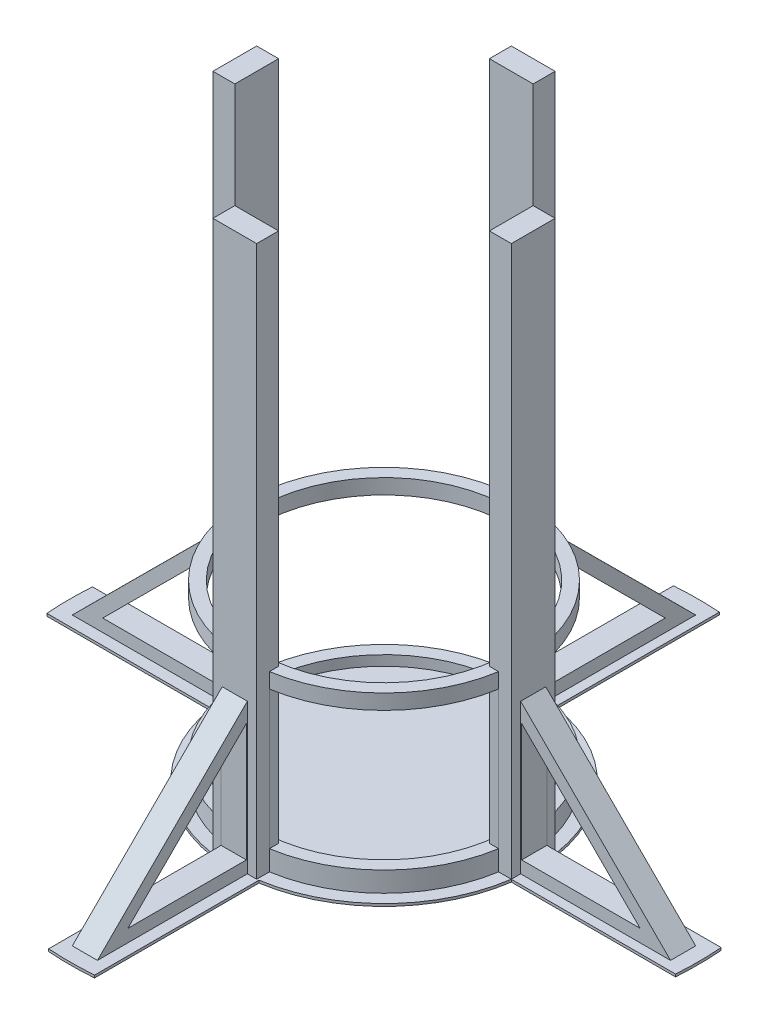
SolidWorks part; units mm, degrees
ref_plane "Front Plane" through (0, 0, 0) normal (0, 0, 1) x (1, 0, 0)
ref_plane "Top Plane" through (0, 0, 0) normal (0, 1, 0) x (1, 0, 0)
ref_plane "Right Plane" through (0, 0, 0) normal (1, 0, 0) x (0, 0, -1)
sketch "Sketch2" plane through (0, 0, 0) normal (0, 1, 0) x (1, 0, 0)
  circle A0 centre (0, 0) radius 55
  dimension "D1" = 110
extrude "Boss-Extrude1" add sketch "Sketch2" along normal blind 70 contours A0
shell "Shell1" thickness 5
sketch "Sketch4" plane through (0, 0, 0) normal (0, 1, 0) x (1, 0, 0)
  circle A0 centre (0, 0) radius 125
  dimension "D1" = 250
extrude "Boss-Extrude2" add sketch "Sketch4" along normal blind 1
sketch "Sketch3" plane through (0, 0, 0) normal (0, 0, 1) x (1, 0, 0)
  line L1 (119, 1) -> (55, 1) construction
  line L3 (55, 64.819) -> (119, 1)
  line L4 (55, 1) -> (55, 70) construction
  line L5 (55, 64.819) -> (55, 1) construction
rib "Rib7" sketch "Sketch3" sketch "Sketch3" thickness 10 extrusion direction parallel to sketch draft on no parameters "D1"=10
pattern_circular "CirPattern1" count 4 every 90 about axis through (0, 0, 0) along (0, 1, 0) of "Rib7"
sketch "Sketch5" plane through (0, 1, 0) normal (0, 1, 0) x (1, 0, 0)
  line L0 (9.4931, -59.2442) -> (9.4931, -129.6529)
  line L1 (59.3646, -8.7092) -> (129.7079, -8.7092)
  line L2 (5, -54.7723) -> (5, -119) construction
  line L3 (54.7723, -5) -> (119, -5) construction
  arc A0 (9.4931, -59.2442) -> (59.3646, -8.7092) centre (0, 0) ccw
  arc A1 (9.4931, -129.6529) -> (129.7079, -8.7092) centre (0, 0) ccw
  dimension "D1" = 120
  dimension "D2" = 130
  dimension "D3" = 70.3434
  dimension "D4" = 70.4087
extrude "Cut-Extrude1" cut sketch "Sketch5" against normal blind 1 contours A0 L1 A1 L0
pattern_circular "CirPattern2" count 4 every 90 about axis through (0, 0, 0) along (0, 1, 0) of "Cut-Extrude1"
sketch "Sketch7" plane through (5, 0, 0) normal (1, 0, 0) x (0, 0, -1)
  line L0 (59.7723, 52.9992) -> (106.9047, 6)
  line L1 (106.9047, 6) -> (59.7723, 6)
  line L2 (59.7723, 6) -> (59.7723, 52.9992)
  line L3 (54.7723, 65.0461) -> (119, 1) construction
  line L4 (54.7723, 1) -> (119, 1) construction
  line L5 (54.7723, 1) -> (54.7723, 65.0461) construction
  line L6 (59.3646, 1) -> (124.6962, 1) construction
  dimension "D1" = 5
  dimension "D2" = 5
  dimension "D3" = 5
extrude "Cut-Extrude2" cut sketch "Sketch7" against normal through all
pattern_circular "CirPattern3" count 4 every 90 about axis through (0, 0, 0) along (0, 1, 0) of "Cut-Extrude2"
sketch "Sketch9" plane through (0, 0, 0) normal (1, 0, 0) x (0, 0, -1)
  line L1 (7.9237, 64.3724) -> (52.7338, 64.3724)
  line L2 (7.9237, 64.3724) -> (7.9237, 5.6452)
  line L3 (7.9237, 5.6452) -> (52.7338, 5.6452)
  line L4 (52.7338, 64.3724) -> (52.7338, 5.6452)
ref_plane "Plane2" through (0, 0, 0) normal (-0.7024, 0, 0.7118) x (0.7118, 0, 0.7024)
sketch "Sketch10" plane through (0, 0, 0) normal (-0.7024, 0, 0.7118) x (0.7118, 0, 0.7024)
  line L0 (-35.4729, 1) -> (-35.4729, 65.0461) construction
  line L1 (-32.4729, 64) -> (31.9142, 64)
  line L2 (-32.4729, 64) -> (-32.4729, 9)
  line L3 (-32.4729, 9) -> (31.9142, 9)
  line L4 (31.9142, 64) -> (31.9142, 9)
  line L5 (34.9142, 1) -> (34.9142, 65.0461) construction
  line L6 (50, 70) -> (-50, 70) construction
  dimension "D1" = 3
  dimension "D2" = 3
  dimension "D3" = 6
  dimension "D4" = 55
extrude "Cut-Extrude3" cut sketch "Sketch10" against normal through all both and the other way through all
pattern_circular "CirPattern4" count 2 every 90 about axis through (0, 70, 0) along (0, 1, 0) of "Cut-Extrude3"
sketch "Sketch11" plane through (0, 70, 0) normal (0, 1, 0) x (1, 0, 0)
  line L1 (50.6354, 8.7092) -> (59.3646, 8.7092)
  line L2 (50.6354, 8.7092) -> (50.6354, -8.7092)
  line L3 (50.6354, -8.7092) -> (59.3646, -8.7092)
  line L4 (59.3646, 8.7092) -> (59.3646, -8.7092)
  line L5 (50.6354, 8.7092) -> (59.3646, -8.7092) construction
  line L6 (50.6354, -8.7092) -> (59.3646, 8.7092) construction
  arc A0 (54.7723, -5) -> (54.7723, 5) centre (0, 0) ccw construction
  point P0 (55, 0)
extrude "Boss-Extrude3" add sketch "Sketch11" along normal blind 150 and the other way up to vertex
pattern_circular "CirPattern5" count 4 every 90 about axis through (0, 0, 0) along (0, 1, 0) of "Boss-Extrude3"
